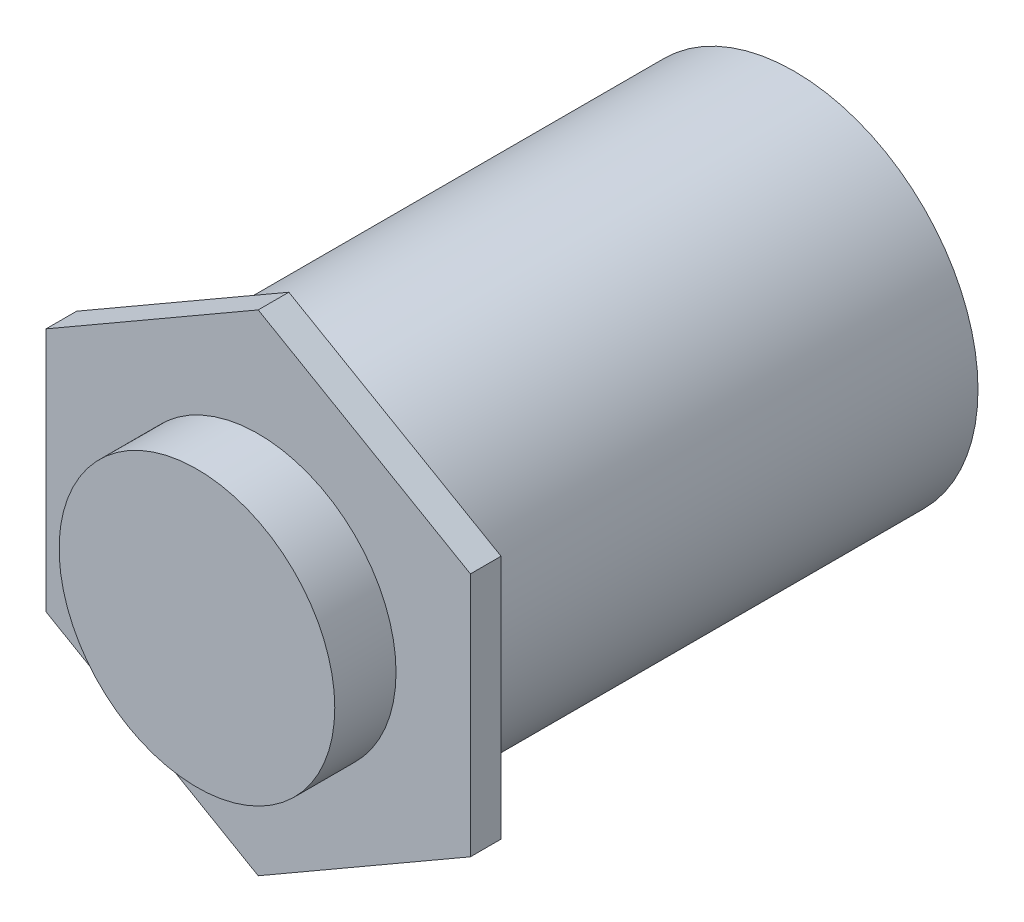
SolidWorks part; units mm, degrees
ref_plane "前视基准面" through (0, 0, 0) normal (0, 0, 1) x (1, 0, 0)
ref_plane "上视基准面" through (0, 0, 0) normal (0, 1, 0) x (1, 0, 0)
ref_plane "右视基准面" through (0, 0, 0) normal (1, 0, 0) x (0, 0, -1)
other "Configuration Table"
sketch "草图1" plane through (0, 0, 0) normal (0, 0, 1) x (1, 0, 0)
  circle A0 centre (0, 0) radius 6
  dimension "D1" = 12
extrude "凸台-拉伸1" add sketch "草图1" along normal blind 16.5
sketch "草图2" plane through (0, 0, 16.5) normal (0, 0, 1) x (1, 0, 0)
  line L1 (0, 8) -> (-6.9282, 4)
  line L2 (-6.9282, 4) -> (-6.9282, -4)
  line L3 (-6.9282, -4) -> (0, -8)
  line L4 (0, -8) -> (6.9282, -4)
  line L5 (6.9282, -4) -> (6.9282, 4)
  line L6 (6.9282, 4) -> (0, 8)
  circle A0 centre (0, 0) radius 6.9282 construction
  dimension "D1" = 16
extrude "凸台-拉伸2" add sketch "草图2" along normal blind 1
sketch "草图3" plane through (0, 0, 17.5) normal (0, 0, 1) x (1, 0, 0)
  circle A0 centre (0, 0) radius 4.5
  dimension "D1" = 9
extrude "凸台-拉伸3" add sketch "草图3" along normal blind 2
